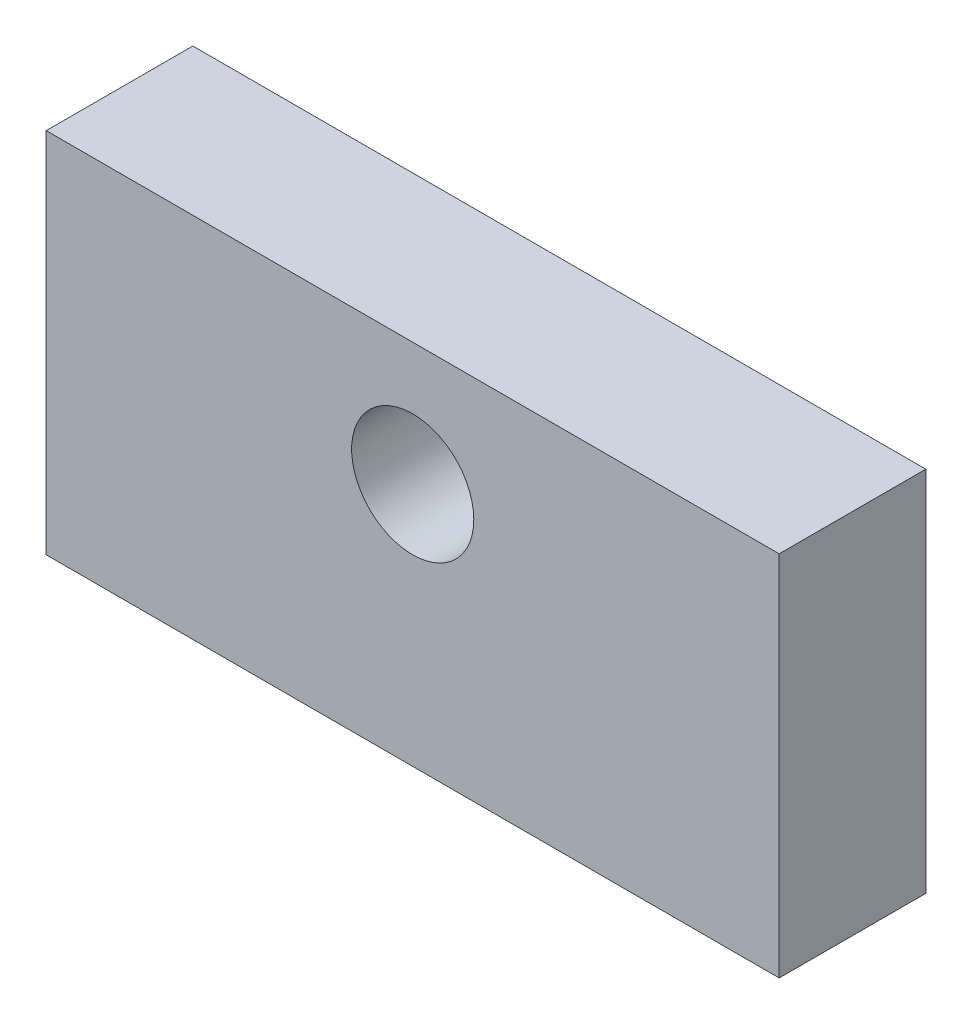
SolidWorks part; units mm, degrees
ref_plane "Спереди" through (0, 0, 0) normal (0, 0, 1) x (1, 0, 0)
ref_plane "Сверху" through (0, 0, 0) normal (0, 1, 0) x (1, 0, 0)
ref_plane "Справа" through (0, 0, 0) normal (1, 0, 0) x (0, 0, -1)
sketch "Эскиз1" plane through (0, 0, 0) normal (0, 0, 1) x (1, 0, 0)
  line L0 (3.4433, 0) -> (3.4433, 9.8965) construction
  line L1 (-11.5567, 3.8903) -> (18.4433, 3.8903)
  line L2 (-11.5567, 3.8903) -> (-11.5567, -11.146)
  line L9 (18.4433, 3.8903) -> (18.4433, -11.146)
  line L10 (-11.5567, -11.146) -> (18.4433, -11.146)
extrude "Вытянуть1" add sketch "Эскиз1" along normal blind 6
sketch "Эскиз2" plane through (0, 0, 6) normal (0, 0, 1) x (1, 0, 0)
  line L0 (0, -1.146) -> (17.0358, -1.146) construction
  circle A0 centre (3.4433, -1.146) radius 2.5
extrude "Вытянуть2" cut sketch "Эскиз2" against normal blind 4
